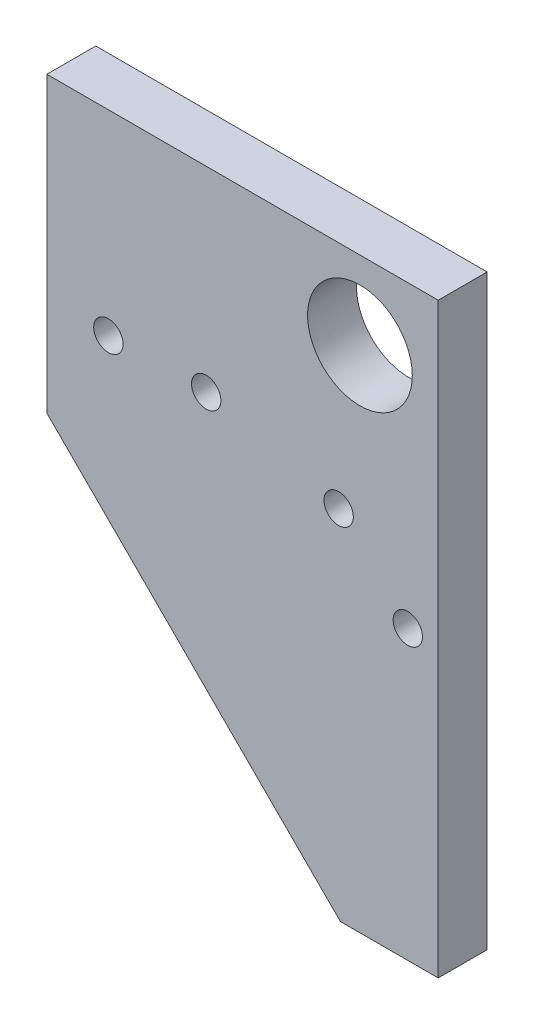
SolidWorks part; units mm, degrees
ref_plane "Front Plane" through (0, 0, 0) normal (0, 0, 1) x (1, 0, 0)
ref_plane "Top Plane" through (0, 0, 0) normal (0, 1, 0) x (1, 0, 0)
ref_plane "Right Plane" through (0, 0, 0) normal (1, 0, 0) x (0, 0, -1)
sketch "Sketch1" plane through (0, 0, 0) normal (0, 0, 1) x (1, 0, 0)
  line L0 (-22.4177, -49.3596) -> (-22.4177, -19.3596)
  line L1 (-22.4177, -19.3596) -> (17.5823, -19.3596)
  line L2 (17.5823, -19.3596) -> (17.5823, -79.3596)
  line L3 (17.5823, -79.3596) -> (7.5823, -79.3596)
  line L4 (7.5823, -79.3596) -> (-22.4177, -49.3596)
  line L5 (-6.1305, -39.3596) -> (3.8695, -39.3596) construction
  line L6 (3.8695, -39.3596) -> (13.2113, -48.7014) construction
  circle A0 centre (-16.1305, -39.3596) radius 1.5
  circle A1 centre (-6.1305, -39.3596) radius 1.5
  circle A2 centre (7.405, -42.8951) radius 1.5
  circle A3 centre (14.4761, -49.9662) radius 1.5
  circle A4 centre (9.5823, -27.3596) radius 4
  dimension "D5" = 3
  dimension "D12" = 8
  dimension "D1" = 135
  dimension "D2" = 10
  dimension "D3" = 40
  dimension "D4" = 30
  dimension "D6" = 20
  dimension "D7" = 10
  dimension "D8" = 10
  dimension "D9" = 135
  dimension "D10" = 5
  dimension "D11" = 10
  dimension "D13" = 8
  dimension "D14" = 8
extrude "Boss-Extrude1" add sketch "Sketch1" along normal blind 5
sketch "Sketch2" plane through (0, 0, 5) normal (0, 0, 1) x (1, 0, 0)
  circle A0 centre (9.5823, -27.3596) radius 5.35
  dimension "D1" = 10.7
extrude "Cut-Extrude1" cut sketch "Sketch2" against normal blind 5
